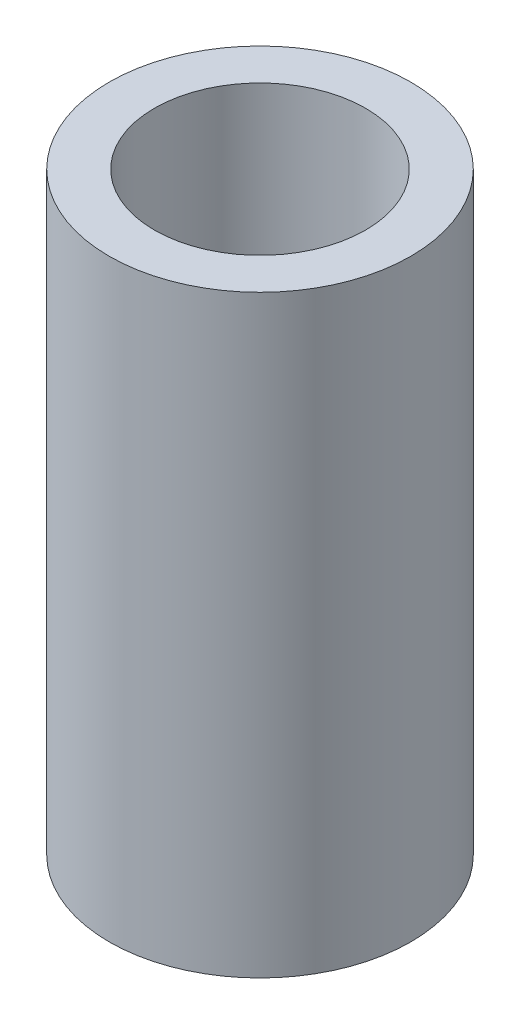
SolidWorks part; units mm, degrees
ref_plane "Front Plane" through (0, 0, 0) normal (0, 0, 1) x (1, 0, 0)
ref_plane "Top Plane" through (0, 0, 0) normal (0, 1, 0) x (1, 0, 0)
ref_plane "Right Plane" through (0, 0, 0) normal (1, 0, 0) x (0, 0, -1)
sketch "Sketch2" plane through (0, 0, 0) normal (0, 1, 0) x (1, 0, 0)
  circle A0 centre (0, 0) radius 2.032
  circle A1 centre (0, 0) radius 2.54
  dimension "D1" = 4.064
  dimension "D2" = 5.08
extrude "Boss-Extrude1" add sketch "Sketch2" along normal blind 10 contours A1
sketch "Sketch3" plane through (0, 10, 0) normal (0, 1, 0) x (1, 0, 0)
  circle A0 centre (0, 0) radius 1.778
  dimension "D1" = 3.556
extrude "Cut-Extrude1" cut sketch "Sketch3" against normal blind 10
